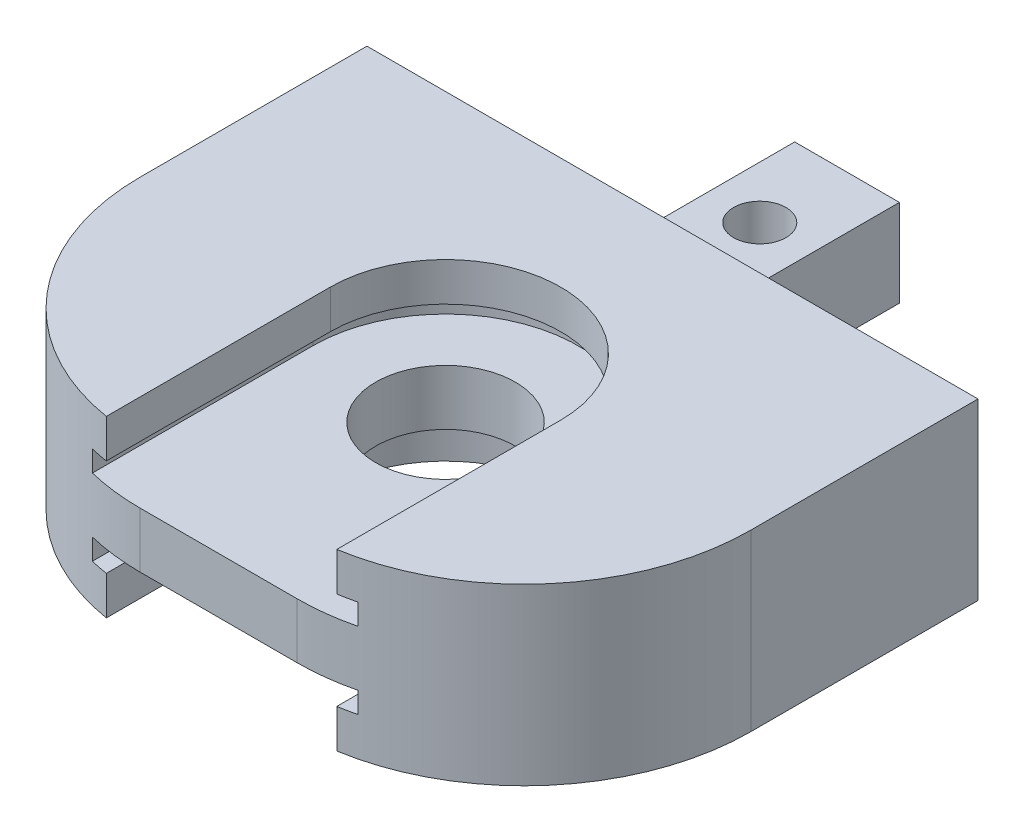
SolidWorks part; units mm, degrees
material "ABS"
ref_plane "Front Plane" through (0, 0, 0) normal (0, 0, 1) x (1, 0, 0)
ref_plane "Top Plane" through (0, 0, 0) normal (0, 1, 0) x (1, 0, 0)
ref_plane "Right Plane" through (0, 0, 0) normal (1, 0, 0) x (0, 0, -1)
sketch "Sketch1" plane through (0, 0, 0) normal (0, 1, 0) x (1, 0, 0)
  line L0 (0, 0) -> (6, 0) construction
  line L1 (6, 0) -> (6, -10) construction
  line L2 (6, -10) -> (12.5, -10)
  line L3 (25, -10) -> (25, 0) construction
  line L4 (25, 0) -> (31, 0) construction
  line L5 (31, 0) -> (31, -10) construction
  line L7 (0, -10) -> (0, 0) construction
  line L8 (0, -10) -> (-2, -10)
  line L11 (33, -36) -> (33, -10)
  line L12 (33, -10) -> (31, -10)
  line L13 (3, 0) -> (3, -5) construction
  line L14 (15.5, -10) -> (15.5, 0) construction
  line L15 (33, -36) -> (-2, -36)
  line L16 (-2, -36) -> (-2, -10)
  line L17 (12.5, -10) -> (12.5, 0)
  line L18 (12.5, 0) -> (18.5, 0)
  line L19 (6, 0) -> (12.5, 0) construction
  line L20 (18.5, 0) -> (18.5, -10)
  line L21 (0, -10) -> (6, -10)
  line L22 (25, -10) -> (31, -10)
  line L23 (18.5, 0) -> (25, 0) construction
  line L24 (18.5, -10) -> (25, -10)
  line L25 (12.5, -10) -> (15.5, -10) construction
  line L26 (15.5, -10) -> (18.5, -10) construction
  circle A0 centre (3, -5) radius 1.5 construction
  circle A1 centre (28, -5) radius 1.5 construction
  circle A2 centre (15.5, -5) radius 1.5
  dimension "D9" = 3
  dimension "D1" = 36
  dimension "D2" = 35
  dimension "D3" = 10
  dimension "D4" = 6
  dimension "D5" = 2
  dimension "D6" = 6
  dimension "D7" = 2
  dimension "D8" = 5
extrude "Boss-Extrude1" add sketch "Sketch1" along normal blind 5
sketch "Sketch2" plane through (0, 0, 36) normal (0, 0, 1) x (1, 0, 0)
  line L0 (-2, 5) -> (-2, 7.5)
  line L1 (-2, 7.5) -> (33, 7.5)
  line L2 (33, 7.5) -> (33, 5)
  line L3 (33, 5) -> (-2, 5)
  line L4 (-2, 0) -> (33, 0)
  line L5 (33, 0) -> (33, -2.5)
  line L6 (33, -2.5) -> (-2, -2.5)
  line L7 (-2, -2.5) -> (-2, 0)
  dimension "D1" = 10
extrude "Boss-Extrude2" add sketch "Sketch2" against normal up to surface (26 mm away) up to face at (5.25, 2.5, 10)
fillet "Fillet1" radius 13 2 edges at (33, 2.5, 36) (-2, 2.5, 36)
ref_plane "Plane1" through (0, 2.5, 0) normal (0, -1, 0) x (-1, 0, 0)
sketch "Sketch3" plane through (0, 0, 36) normal (0, 0, -1) x (-1, 0, 0)
  line L0 (-22.1, 7.5) -> (-22.1, 5.2875)
  line L1 (2, 7.5) -> (-33, 7.5) construction
  line L2 (-22.1, 5.2875) -> (-23.1, 5.2875)
  line L3 (-23.1, 5.2875) -> (-23.1, 4.0875)
  line L4 (-23.1, 4.0875) -> (-15.5, 4.0875)
  line L5 (-15.5, 4.0875) -> (-7.9, 4.0875)
  line L6 (-7.9, 4.0875) -> (-7.9, 5.2875)
  line L7 (-7.9, 5.2875) -> (-8.9, 5.2875)
  line L8 (-8.9, 5.2875) -> (-8.9, 7.5)
  line L9 (-8.9, 7.5) -> (-22.1, 7.5)
  line L10 (-12.5, 0) -> (-18.5, 0) construction
  line L13 (-15.5, 0) -> (-15.5, 4.0875) construction
  dimension "D1" = 1.2
  dimension "D2" = 3.4125
  dimension "D3" = 13.2
  dimension "D4" = 15.2
extrude "Cut-Extrude1" cut sketch "Sketch3" along normal blind 13
sketch "Sketch4" plane through (0, 4.0875, 0) normal (0, 1, 0) x (1, 0, 0)
  line L0 (8.9, -23) -> (22.1, -23) construction
  circle A0 centre (15.5, -23) radius 7.6
  dimension "D1" = 15.2
extrude "Cut-Extrude2" cut sketch "Sketch4" along normal up to surface (1.2 mm away) up to face at (8.3995, 5.2875, 29.366)
sketch "Sketch5" plane through (0, 4.0875, 0) normal (0, 1, 0) x (1, 0, 0)
  line L0 (8.9, -23) -> (22.1, -23) construction
  circle A0 centre (15.5, -23) radius 6.6
  dimension "D1" = 13.2
extrude "Cut-Extrude3" cut sketch "Sketch5" along normal through all
mirror "Mirror1" about plane through (0, 2.5, 0) normal (0, -1, 0) of "Cut-Extrude1"
sketch "Sketch6" plane through (0, 0.9125, 0) normal (0, -1, 0) x (1, 0, 0)
  line L0 (8.9, 23) -> (22.1, 23) construction
  circle A0 centre (15.5, 23) radius 7.6
  dimension "D1" = 15.2
extrude "Cut-Extrude4" cut sketch "Sketch6" along normal up to surface (1.2 mm away) up to face at (8.3995, -0.2875, 29.366)
sketch "Sketch7" plane through (0, 0.9125, 0) normal (0, -1, 0) x (1, 0, 0)
  line L0 (8.9, 23) -> (22.1, 23) construction
  circle A0 centre (15.5, 23) radius 6.6
  dimension "D1" = 13.2
extrude "Cut-Extrude5" cut sketch "Sketch7" along normal through all
sketch "Sketch8" plane through (0, 4.0875, 0) normal (0, 1, 0) x (1, 0, 0)
  circle A0 centre (15.5, -23) radius 4
  dimension "D1" = 8
extrude "Cut-Extrude6" cut sketch "Sketch8" against normal through all
